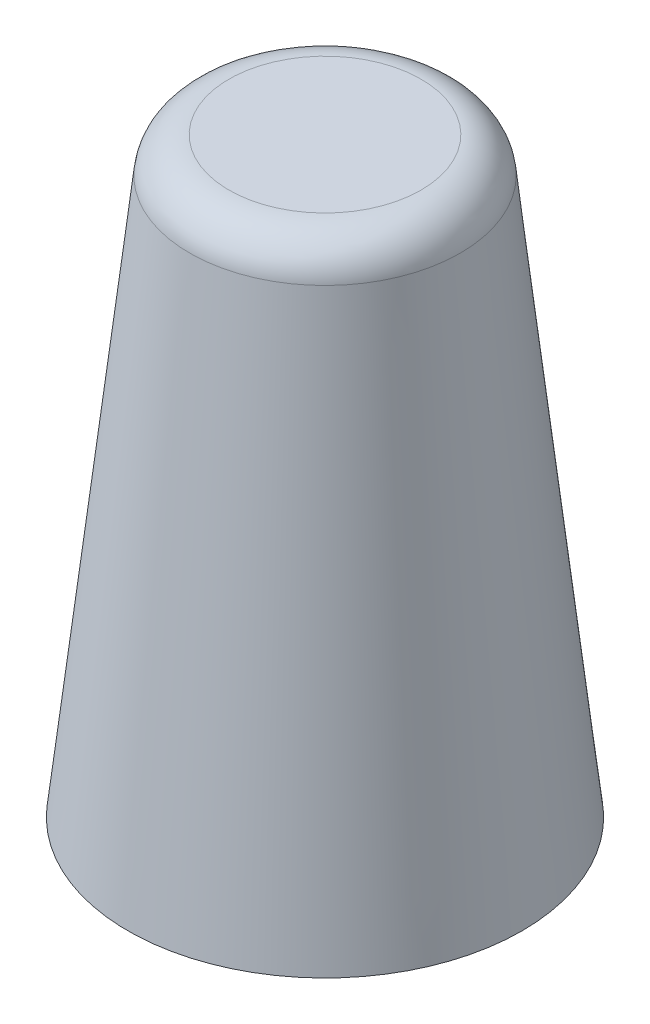
SolidWorks part; units mm, degrees
ref_plane "Спереди" through (0, 0, 0) normal (0, 0, 1) x (1, 0, 0)
ref_plane "Сверху" through (0, 0, 0) normal (0, 1, 0) x (1, 0, 0)
ref_plane "Справа" through (0, 0, 0) normal (1, 0, 0) x (0, 0, -1)
sketch "Эскиз1" plane through (0, 0, 0) normal (0, 0, 1) x (1, 0, 0)
  line L0 (0, -451.658) -> (0, 22131.2437) construction
  line L1 (0, 0) -> (15, 0)
  line L2 (15, 0) -> (10.2965, 42.3313)
  line L3 (7.3149, 45) -> (0, 45)
  line L4 (0, 45) -> (0, 0)
  arc A0 (10.2965, 42.3313) -> (7.3149, 45) centre (7.3149, 42) ccw
  point P9 (10, 45)
  dimension "D4" = 3
  dimension "D1" = 15
  dimension "D2" = 45
  dimension "D3" = 10
revolve "Повернуть2" add sketch "Эскиз1" angle 360 about L0
